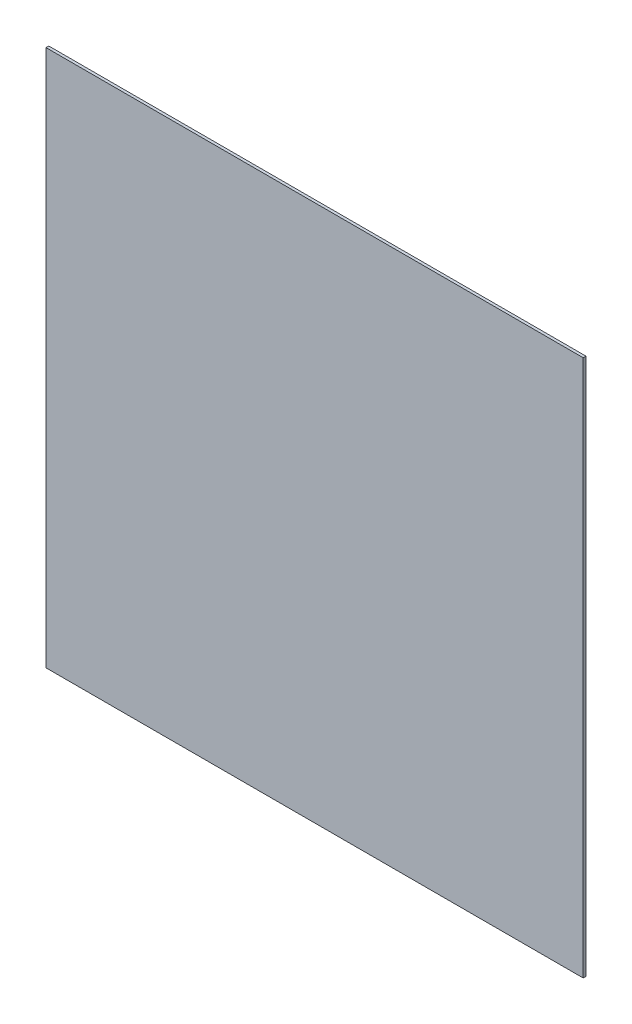
SolidWorks part; units mm, degrees
ref_plane "Front Plane" through (0, 0, 0) normal (0, 0, 1) x (1, 0, 0)
ref_plane "Top Plane" through (0, 0, 0) normal (0, 1, 0) x (1, 0, 0)
ref_plane "Right Plane" through (0, 0, 0) normal (1, 0, 0) x (0, 0, -1)
sketch "Sketch1" plane through (0, 0, 0) normal (0, 0, 1) x (1, 0, 0)
  line L1 (-307.975, -307.975) -> (307.975, -307.975)
  line L2 (-307.975, -307.975) -> (-307.975, 307.975)
  line L3 (-307.975, 307.975) -> (307.975, 307.975)
  line L4 (307.975, -307.975) -> (307.975, 307.975)
  line L5 (-307.975, -307.975) -> (307.975, 307.975) construction
  line L6 (-307.975, 307.975) -> (307.975, -307.975) construction
  point P0 (0, 0)
  dimension "D1" = 615.95
extrude "Boss-Extrude1" add sketch "Sketch1" along normal blind 3.175
